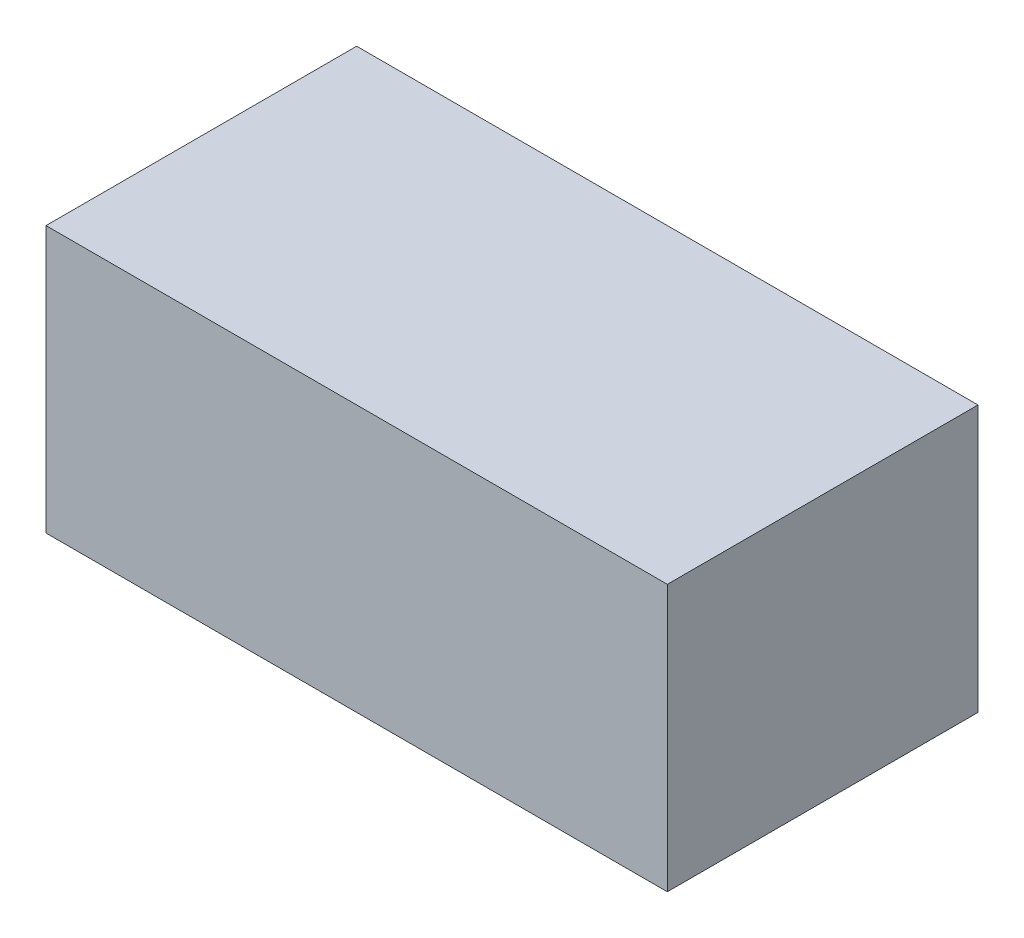
SolidWorks part; units mm, degrees
ref_plane "前视基准面" through (0, 0, 0) normal (0, 0, 1) x (1, 0, 0)
ref_plane "上视基准面" through (0, 0, 0) normal (0, 1, 0) x (1, 0, 0)
ref_plane "右视基准面" through (0, 0, 0) normal (1, 0, 0) x (0, 0, -1)
sketch "草图1" plane through (0, 0, 0) normal (0, 1, 0) x (1, 0, 0)
  line L1 (-35, 17.5) -> (35, 17.5)
  line L2 (-35, 17.5) -> (-35, -17.5)
  line L3 (-35, -17.5) -> (35, -17.5)
  line L4 (35, 17.5) -> (35, -17.5)
  line L5 (-35, 17.5) -> (35, -17.5) construction
  line L6 (-35, -17.5) -> (35, 17.5) construction
  point P0 (0, 0)
  dimension "D1" = 70
  dimension "D2" = 35
extrude "凸台-拉伸1" add sketch "草图1" along normal blind 30
